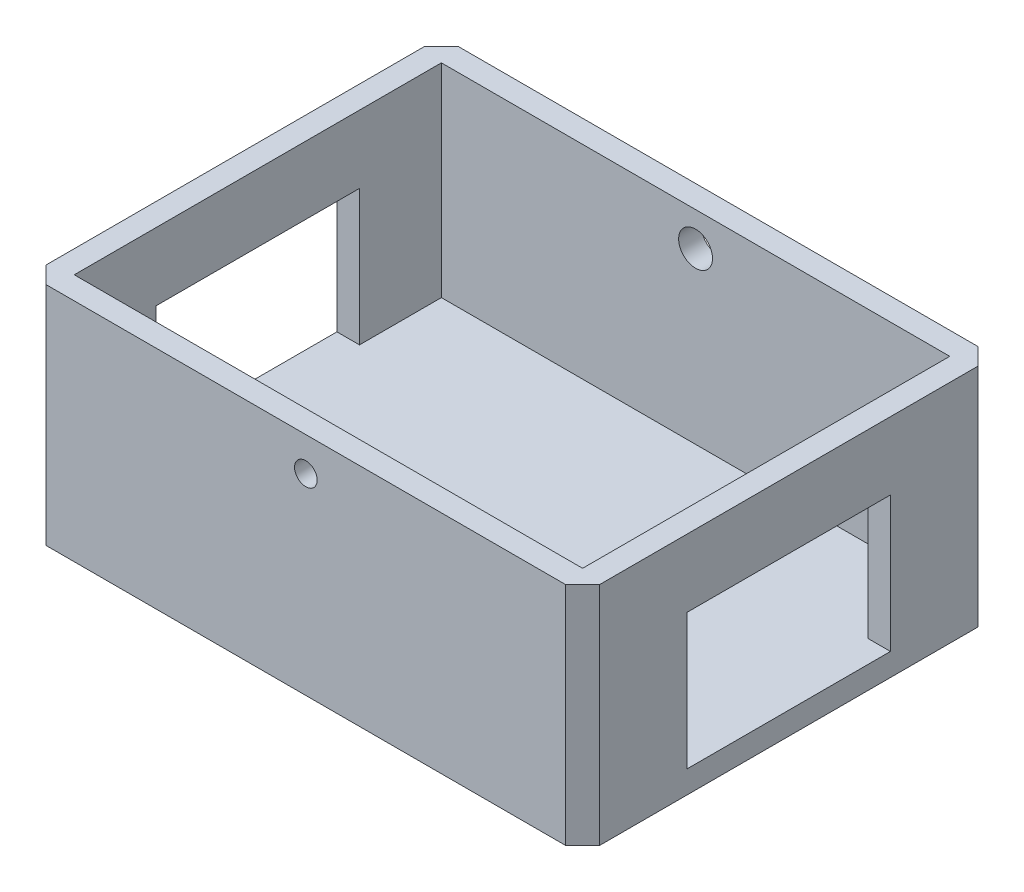
SolidWorks part; units mm, degrees
material "ABS"
ref_plane "Front Plane" through (0, 0, 0) normal (0, 0, 1) x (1, 0, 0)
ref_plane "Top Plane" through (0, 0, 0) normal (0, 1, 0) x (1, 0, 0)
ref_plane "Right Plane" through (0, 0, 0) normal (1, 0, 0) x (0, 0, -1)
sketch "Sketch1" plane through (0, 0, 0) normal (0, 1, 0) x (1, 0, 0)
  line L1 (-12.25, 9.125) -> (12.25, 9.125)
  line L2 (-12.25, 9.125) -> (-12.25, -9.125)
  line L3 (-12.25, -9.125) -> (12.25, -9.125)
  line L4 (12.25, 9.125) -> (12.25, -9.125)
  line L5 (-12.25, 9.125) -> (12.25, -9.125) construction
  line L6 (-12.25, -9.125) -> (12.25, 9.125) construction
  point P0 (0, 0)
  dimension "D1" = 18.25
  dimension "D2" = 24.5
extrude "Boss-Extrude1" add sketch "Sketch1" along normal blind 10
shell "Shell4" thickness 1
chamfer "Chamfer1" distance 0.75 angle 45 4 edges at (-12.25, 5, 9.125) (-12.25, 5, -9.125) (12.25, 5, -9.125) (12.25, 5, 9.125)
sketch "Sketch8" plane through (0, 0, -8.125) normal (0, 0, 1) x (1, 0, 0)
  line L0 (11.25, 10) -> (-11.25, 10) construction
  circle A0 centre (0, 8.5) radius 0.75
  point P4 (0, 10)
  dimension "D1" = 1.5
extrude "Cut-Extrude2" cut sketch "Sketch8" against normal up to next
sketch "Sketch9" plane through (0, 0, 9.125) normal (0, 0, 1) x (1, 0, 0)
  line L0 (-11.5, 10) -> (11.5, 10) construction
  circle A0 centre (0, 8.5) radius 0.5
  dimension "D1" = 1.5
extrude "Cut-Extrude3" cut sketch "Sketch9" against normal up to next
sketch "Sketch10" plane through (12.25, 0, 0) normal (1, 0, 0) x (0, 0, -1)
  line L0 (0, 5.5) -> (0, -5.5) construction
  line L1 (-4.5, 7) -> (4.5, 7)
  line L2 (-4.5, 7) -> (-4.5, 1)
  line L3 (-4.5, 1) -> (4.5, 1)
  line L4 (4.5, 7) -> (4.5, 1)
  line L5 (-4.5, 7) -> (4.5, 1) construction
  line L6 (-4.5, 1) -> (4.5, 7) construction
  line L7 (10.0375, 0) -> (-10.0375, 0) construction
  point P0 (0, 4)
  dimension "D1" = 4.5
  dimension "D2" = 4.5
  dimension "D3" = 7
  dimension "D4" = 1
extrude "Cut-Extrude4" cut sketch "Sketch10" against normal up to next
mirror "Mirror1" about plane through (0, 0, 0) normal (1, 0, 0) of "Cut-Extrude4"
